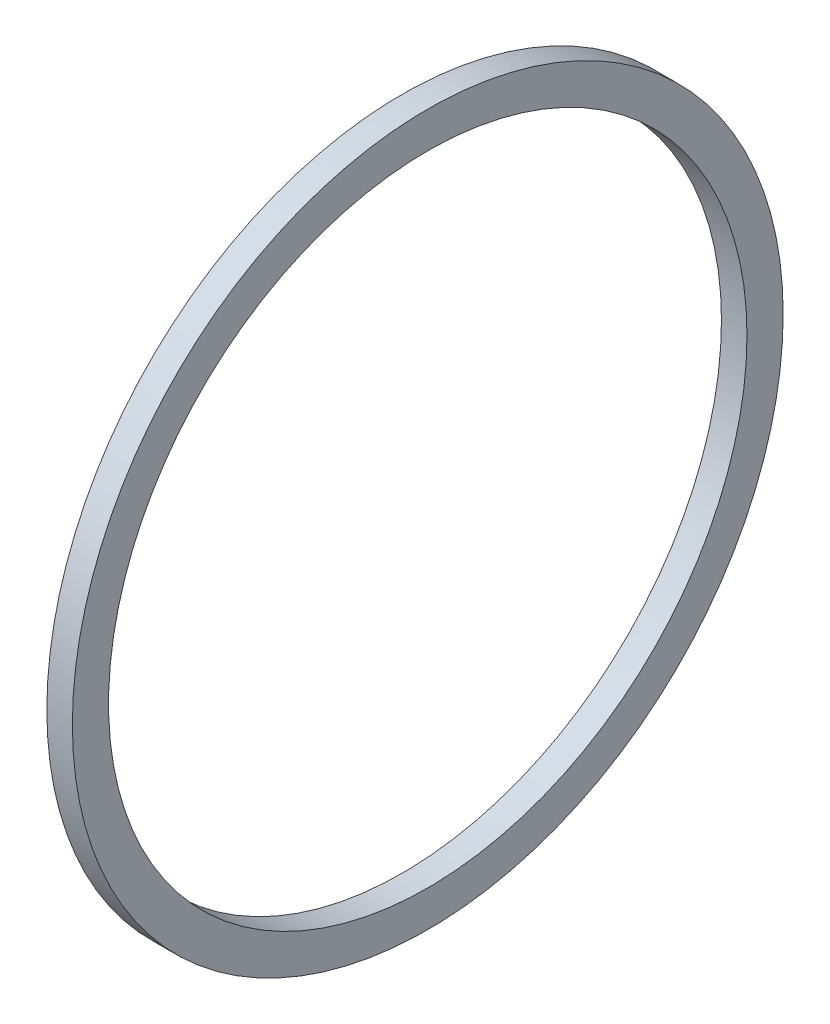
SolidWorks part; units mm, degrees
ref_plane "Front Plane" through (0, 0, 0) normal (0, 0, 1) x (1, 0, 0)
ref_plane "Top Plane" through (0, 0, 0) normal (0, 1, 0) x (1, 0, 0)
ref_plane "Right Plane" through (0, 0, 0) normal (1, 0, 0) x (0, 0, -1)
sketch "Sketch1" plane through (0, 0, 0) normal (1, 0, 0) x (0, 0, -1)
  circle A0 centre (0, 0) radius 16.7
  circle A1 centre (0, 0) radius 15
  dimension "D1" = 33.4
  dimension "D2" = 30
extrude "Boss-Extrude1" add sketch "Sketch1" along normal blind 1.2
